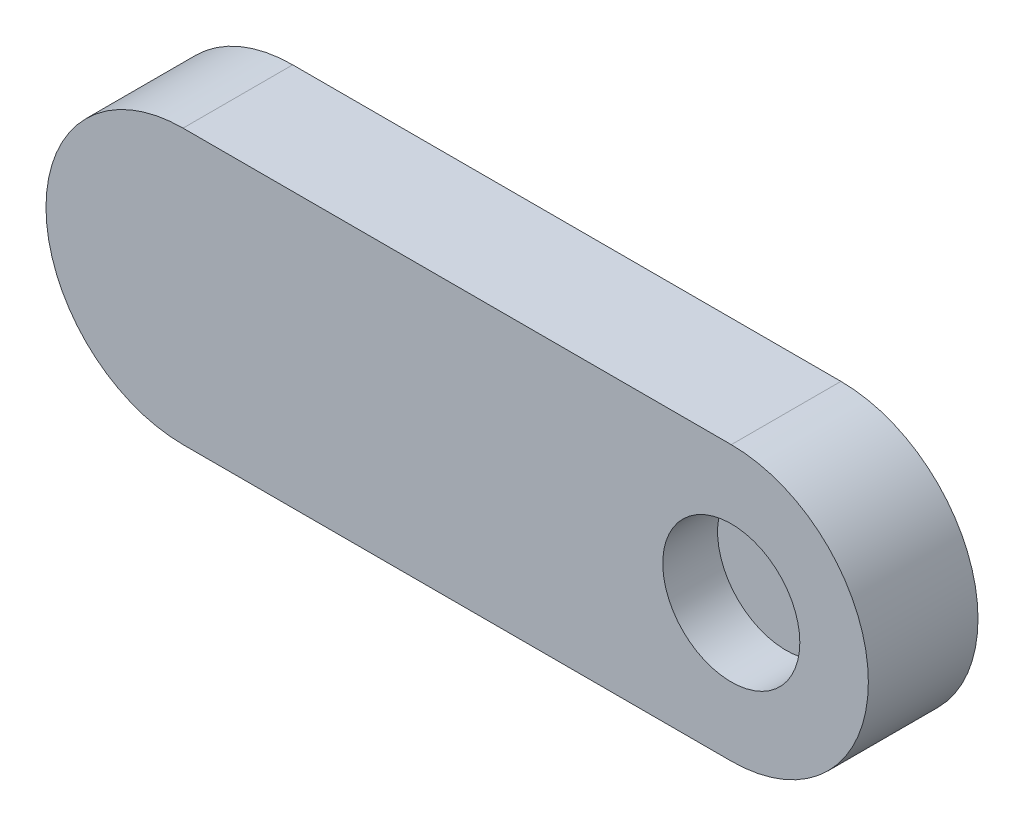
SolidWorks part; units mm, degrees
ref_plane "前视基准面" through (0, 0, 0) normal (0, 0, 1) x (1, 0, 0)
ref_plane "上视基准面" through (0, 0, 0) normal (0, 1, 0) x (1, 0, 0)
ref_plane "右视基准面" through (0, 0, 0) normal (1, 0, 0) x (0, 0, -1)
sketch "草图1" plane through (0, 0, 0) normal (0, 0, 1) x (1, 0, 0)
  line L0 (0, 0) -> (200, 0) construction
  line L1 (0, 50) -> (200, 50)
  line L2 (0, -50) -> (200, -50)
  arc A0 (0, 50) -> (0, -50) centre (0, 0) ccw
  arc A1 (200, -50) -> (200, 50) centre (200, 0) ccw
  point P3 (100, 0)
  dimension "D1" = 50
  dimension "D2" = 200
extrude "凸台-拉伸1" add sketch "草图1" along normal blind 40
sketch "草图2" plane through (0, 0, 0) normal (0, 0, -1) x (-1, 0, 0)
  circle A0 centre (0, 0) radius 25
  point P5 (0, 0)
  dimension "D2" = 50
extrude "切除-拉伸1" cut sketch "草图2" against normal blind 20
sketch "草图3" plane through (0, 0, 40) normal (0, 0, 1) x (1, 0, 0)
  circle A0 centre (200, 0) radius 25
  point P2 (0, 0)
  dimension "D1" = 50
extrude "切除-拉伸2" cut sketch "草图3" against normal blind 20
